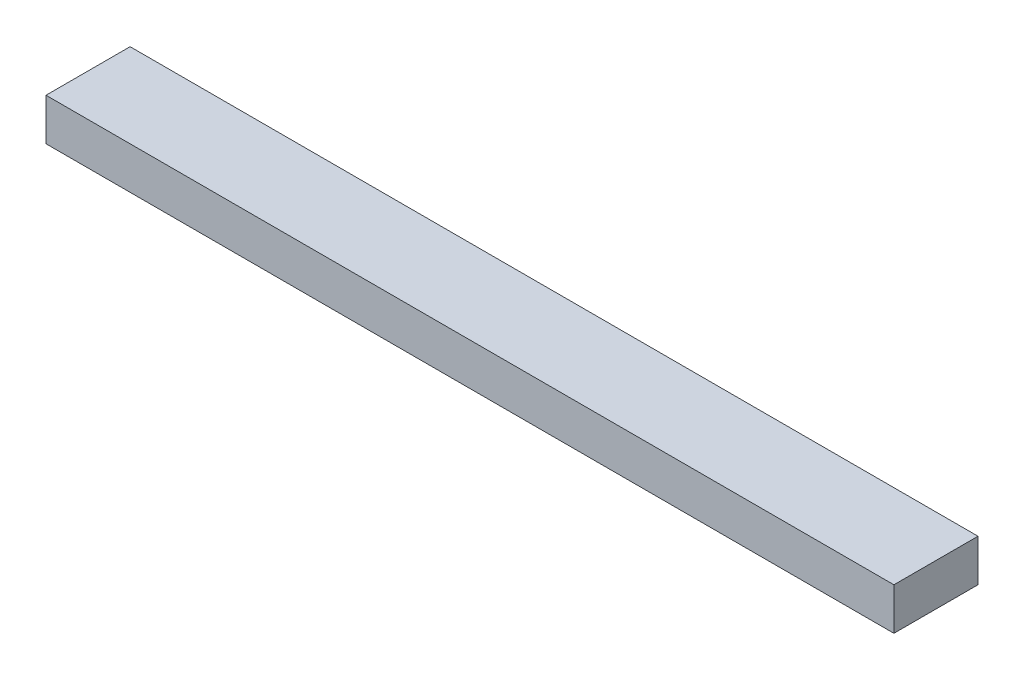
SolidWorks part; units mm, degrees
ref_plane "Plan de face" through (0, 0, 0) normal (0, 0, 1) x (1, 0, 0)
ref_plane "Plan de dessus" through (0, 0, 0) normal (0, 1, 0) x (1, 0, 0)
ref_plane "Plan de droite" through (0, 0, 0) normal (1, 0, 0) x (0, 0, -1)
sketch "Esquisse1" plane through (0, 0, 0) normal (0, 1, 0) x (1, 0, 0)
  line L1 (60.5, 6) -> (-60.5, 6)
  line L2 (60.5, 6) -> (60.5, -6)
  line L3 (60.5, -6) -> (-60.5, -6)
  line L4 (-60.5, 6) -> (-60.5, -6)
  line L5 (60.5, 6) -> (-60.5, -6) construction
  line L6 (60.5, -6) -> (-60.5, 6) construction
  point P0 (0, 0)
  dimension "D1" = 121
  dimension "D2" = 12
extrude "Boss.-Extru.1" add sketch "Esquisse1" along normal blind 6
